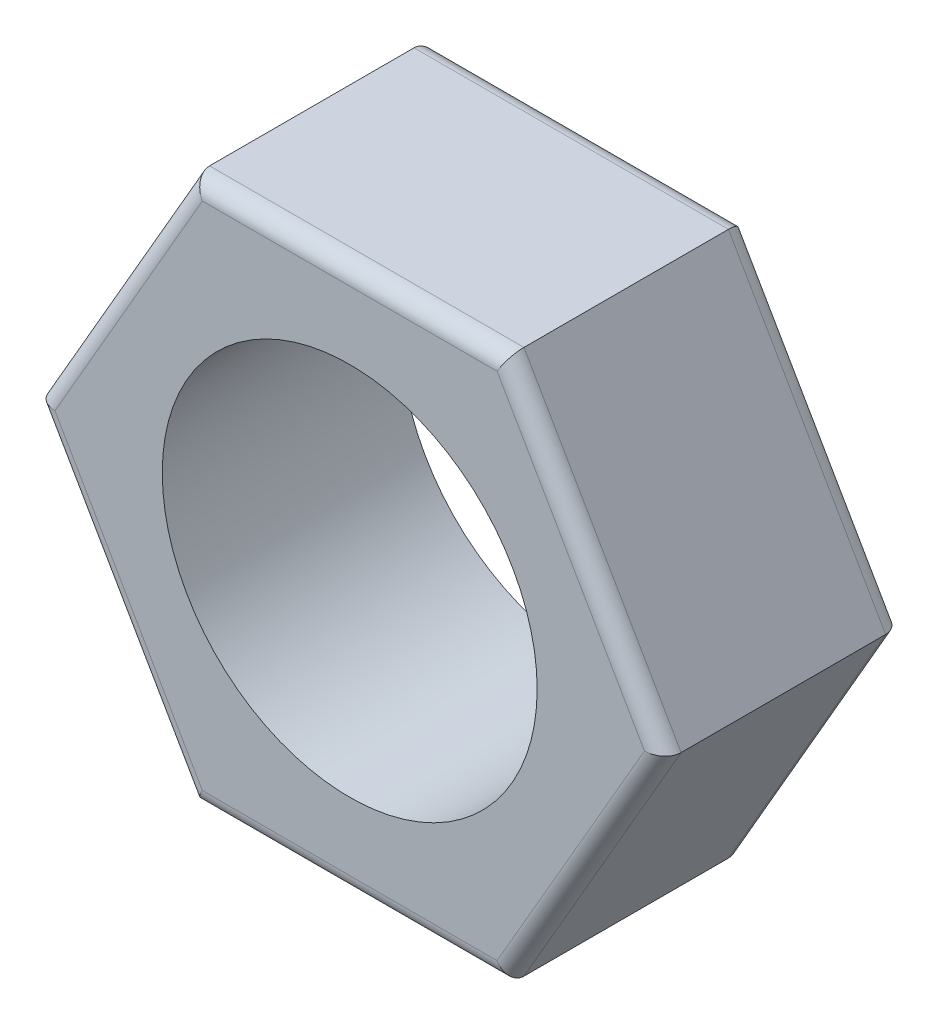
SolidWorks part; units mm, degrees
ref_plane "前视基准面" through (0, 0, 0) normal (0, 0, 1) x (1, 0, 0)
ref_plane "上视基准面" through (0, 0, 0) normal (0, 1, 0) x (1, 0, 0)
ref_plane "右视基准面" through (0, 0, 0) normal (1, 0, 0) x (0, 0, -1)
sketch "草图2" plane through (0, 0, 0) normal (0, 0, 1) x (1, 0, 0)
  line L1 (9.225, -15.9782) -> (18.45, 0)
  line L2 (18.45, 0) -> (9.225, 15.9782)
  line L3 (9.225, 15.9782) -> (-9.225, 15.9782)
  line L4 (-9.225, 15.9782) -> (-18.45, 0)
  line L5 (-18.45, 0) -> (-9.225, -15.9782)
  line L6 (-9.225, -15.9782) -> (9.225, -15.9782)
  circle A0 centre (0, 0) radius 15.9782 construction
  dimension "D1" = 36.9
extrude "拉伸1" add sketch "草图2" along normal blind 14
sketch "草图3" plane through (0, 0, 0) normal (0, 0, -1) x (-1, 0, 0)
  circle A0 centre (0, 0) radius 11
  dimension "D1" = 22
extrude "拉伸2" cut sketch "草图3" against normal through all
fillet "圆角1" radius 1 12 edges at (0, -15.9782, 14) (-13.8375, -7.9891, 14) (-13.8375, 7.9891, 14) (-13.8375, -7.9891, 0) (0, -15.9782, 0) (13.8375, -7.9891, 0) (13.8375, 7.9891, 0) (0, 15.9782, 0) (-13.8375, 7.9891, 0) (13.8375, -7.9891, 14) (13.8375, 7.9891, 14) (0, 15.9782, 14)
